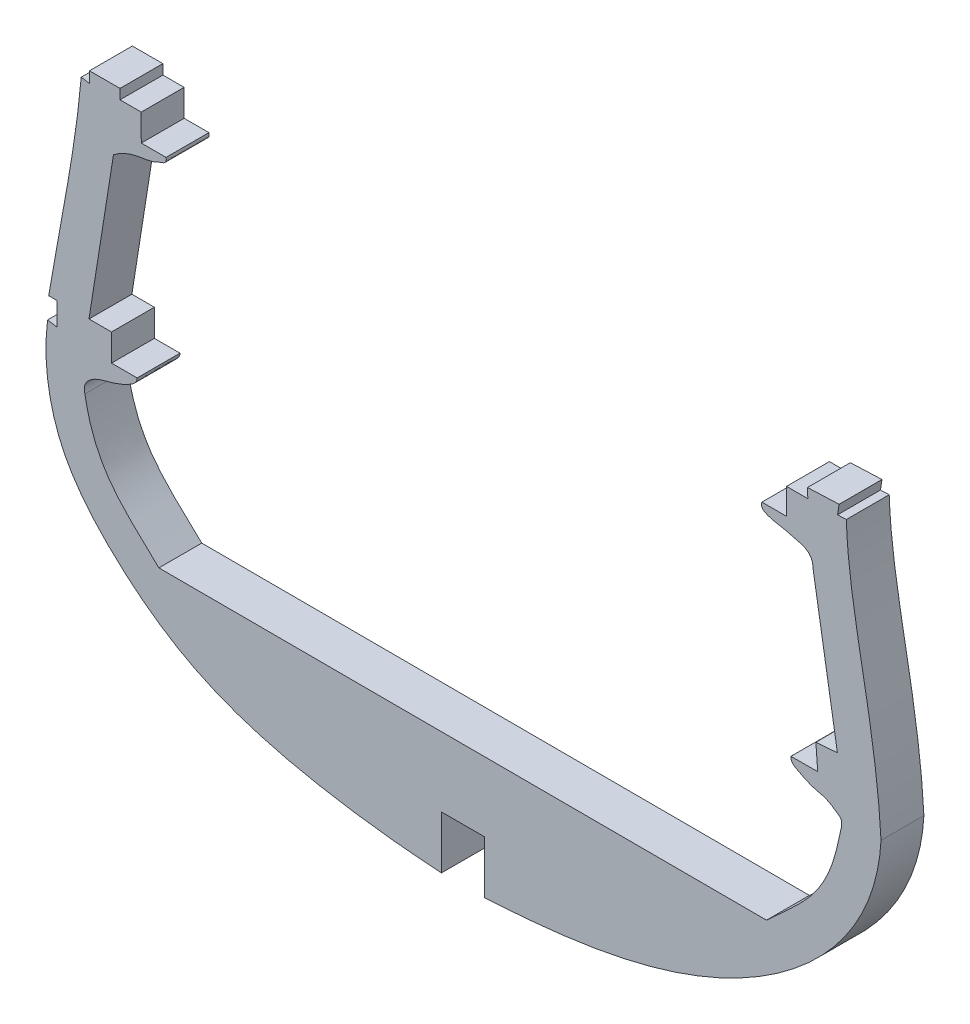
SolidWorks part; units mm, degrees
ref_plane "前视基准面" through (0, 0, 0) normal (0, 0, 1) x (1, 0, 0)
ref_plane "上视基准面" through (0, 0, 0) normal (0, 1, 0) x (1, 0, 0)
ref_plane "右视基准面" through (0, 0, 0) normal (1, 0, 0) x (0, 0, -1)
other "Configuration Table"
sketch "草图1" plane through (0, 0, 0) normal (0, 0, 1) x (1, 0, 0)
  line L0 (376.5, 617) -> (1882.5, 617) construction
  line L1 (1400.6038, 978.4164) -> (1400.5994, 988.2636)
  line L3 (1392.5997, 988.2636) -> (1392.6041, 978.418)
  line L4 (1453.2255, 1001.0989) -> (1339.8953, 1001.335)
  line L5 (1319.1353, 1031.0046) -> (1320.9072, 1030.724)
  line L6 (1320.9072, 1030.724) -> (1320.9053, 1035.0112)
  line L7 (1320.9053, 1035.0112) -> (1319.3434, 1035.0105)
  line L8 (1325.4158, 1073.3501) -> (1326.949, 1073.1072)
  line L9 (1326.949, 1073.1072) -> (1326.9481, 1075.1514)
  line L10 (1326.9481, 1075.1514) -> (1332.6459, 1075.1539)
  line L11 (1332.6459, 1075.1539) -> (1332.6467, 1073.3055)
  line L12 (1332.6467, 1073.3055) -> (1336.608, 1073.3073)
  line L13 (1336.608, 1073.3073) -> (1336.6103, 1068.303)
  line L14 (1336.6103, 1068.303) -> (1341.2347, 1068.3051)
  line L15 (1331.4254, 1063.8226) -> (1326.8631, 1035.0176)
  line L16 (1326.8631, 1035.0176) -> (1331.058, 1035.0195)
  line L17 (1331.058, 1035.0195) -> (1331.0602, 1029.9851)
  line L18 (1331.0602, 1029.9851) -> (1335.8413, 1029.9873)
  line L19 (1468.1093, 1073.2543) -> (1466.4663, 1073.1864)
  line L20 (1466.4663, 1073.1864) -> (1466.7601, 1075.0409)
  line L21 (1466.7601, 1075.0409) -> (1460.856, 1074.7969)
  line L22 (1460.856, 1074.7969) -> (1460.929, 1073.0294)
  line L23 (1460.929, 1073.0294) -> (1456.9493, 1073.0277)
  line L24 (1456.9493, 1073.0277) -> (1456.9514, 1068.1931)
  line L25 (1456.9514, 1068.1931) -> (1452.3621, 1068.191)
  line L26 (1461.8895, 1062.3225) -> (1466.4463, 1034.7431)
  line L27 (1466.4463, 1034.7431) -> (1462.4243, 1034.4389)
  line L28 (1462.4243, 1034.4389) -> (1462.7701, 1029.8656)
  line L29 (1462.7701, 1029.8656) -> (1457.7779, 1029.8415)
  line L30 (1392.5997, 988.2636) -> (1400.5994, 988.2636)
  spline S0 degree 3 poles (1392.6041, 978.418) (1384.3017, 978.9473) (1368.9128, 980.7051) (1347.0372, 986.748) (1331.7793, 998.008) (1319.8391, 1012.2292) (1318.2885, 1024.3418) (1319.1353, 1031.0046) knots 0 0 0 0 0.246033 0.460162 0.662189 0.799061 1 1 1 1
  spline S1 degree 3 poles (1319.3434, 1035.0105) (1321.4342, 1047.7802) (1324.2981, 1060.4321) (1325.4158, 1073.3501) knots 0 0 0 0 1 1 1 1
  spline S2 degree 3 poles (1341.2347, 1068.3051) (1341.4842, 1067.2406) (1340.2869, 1067.1075) (1339.0021, 1066.4181) (1337.4757, 1066.0468) (1334.7261, 1065.7518) (1332.5962, 1064.7384) (1331.4254, 1063.8226) knots 0 0 0 0 0.192767 0.263443 0.393742 0.603766 1 1 1 1
  spline S3 degree 3 poles (1335.8413, 1029.9873) (1335.824, 1029.1137) (1333.9342, 1027.8406) (1331.0959, 1026.7645) (1327.5085, 1026.0087) (1325.6092, 1024.0749) (1326.1023, 1022.5334) knots 0 0 0 0 0.176555 0.474168 0.69551 1 1 1 1
  spline S4 degree 3 poles (1326.1023, 1022.5334) (1326.6881, 1019.0287) (1329.4048, 1010.5372) (1336.3227, 1004.7816) (1339.8953, 1001.335) knots 0 0 0 0 0.415295 1 1 1 1
  spline S5 degree 3 poles (1400.6038, 978.4164) (1415.9631, 979.2778) (1447.9424, 983.2279) (1473.6415, 1007.5028) (1474.5778, 1024.676) knots 0 0 0 0 0.489063 1 1 1 1
  spline S6 degree 3 poles (1474.5778, 1024.676) (1474.1798, 1032.3961) (1471.7095, 1048.5719) (1468.3775, 1064.6036) (1468.1093, 1073.2543) knots 0 0 0 0 0.47246 1 1 1 1
  spline S7 degree 3 poles (1452.3621, 1068.191) (1452.0632, 1067.292) (1453.5506, 1066.3958) (1456.0012, 1066.0676) (1459.2553, 1065.2451) (1461.8502, 1064.5371) (1461.8895, 1062.3225) knots 0 0 0 0 0.172002 0.374139 0.617871 1 1 1 1
  spline S8 degree 3 poles (1453.2255, 1001.0989) (1456.416, 1004.1959) (1461.7705, 1008.2289) (1465.7723, 1016.3522) (1466.6757, 1020.7716) (1467.4619, 1024.2835) (1465.7321, 1025.5175) (1464.6494, 1026.2098) (1463.5637, 1026.4917) knots 0 0 0 0 0.417473 0.611309 0.814395 0.872955 0.89966 1 1 1 1
  spline S9 degree 3 poles (1457.7779, 1029.8415) (1457.6915, 1028.9353) (1459.9559, 1027.6885) (1461.8139, 1026.8231) (1463.5637, 1026.4917) knots 0 0 0 0 0.320094 1 1 1 1
  dimension "D3" = 9.8472
extrude "凸台-拉伸1" add sketch "草图1" along normal blind 8
